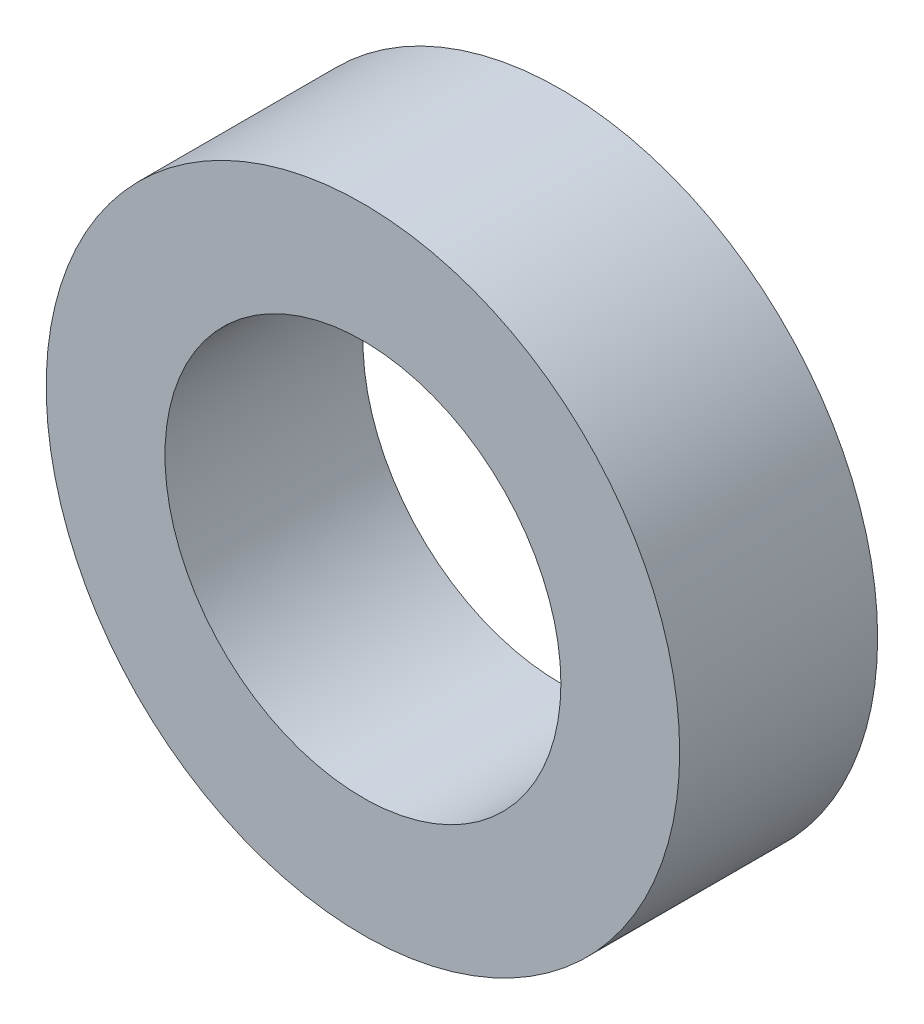
SolidWorks part; units mm, degrees
ref_plane "Front Plane" through (0, 0, 0) normal (0, 0, 1) x (1, 0, 0)
ref_plane "Top Plane" through (0, 0, 0) normal (0, 1, 0) x (1, 0, 0)
ref_plane "Right Plane" through (0, 0, 0) normal (1, 0, 0) x (0, 0, -1)
sketch "Sketch1" plane through (0, 0, 0) normal (0, 0, 1) x (1, 0, 0)
  circle A0 centre (0, 0) radius 4
  circle A1 centre (0, 0) radius 2.5
  dimension "D1" = 8
extrude "Boss-Extrude1" add sketch "Sketch1" along normal blind 2.5 contours A0 A1
